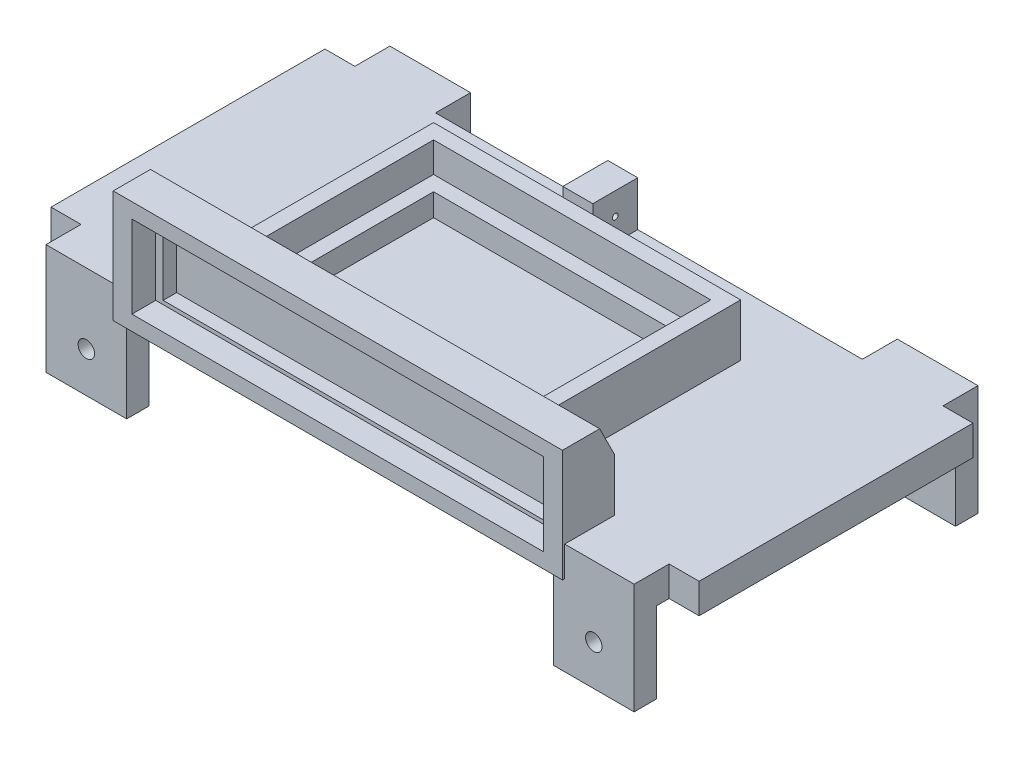
SolidWorks part; units mm, degrees
ref_plane "Front Plane" through (0, 0, 0) normal (0, 0, 1) x (1, 0, 0)
ref_plane "Top Plane" through (0, 0, 0) normal (0, 1, 0) x (1, 0, 0)
ref_plane "Right Plane" through (0, 0, 0) normal (1, 0, 0) x (0, 0, -1)
sketch "Sketch1" plane through (0, 0, 0) normal (1, 0, 0) x (0, 0, -1)
  line L0 (18.2875, 20.8275) -> (-18.2875, 20.8275)
  line L1 (14.2875, -16.8275) -> (-14.2875, -16.8275)
  line L2 (14.2875, -16.8275) -> (14.2875, 16.8275)
  line L3 (14.2875, 16.8275) -> (-14.2875, 16.8275)
  line L4 (-14.2875, -16.8275) -> (-14.2875, 16.8275)
  line L5 (14.2875, -16.8275) -> (-14.2875, 16.8275) construction
  line L6 (14.2875, 16.8275) -> (-14.2875, -16.8275) construction
  line L7 (-18.2875, -20.8275) -> (-18.2875, 20.8275)
  line L8 (18.2875, -20.8275) -> (-18.2875, -20.8275)
  line L9 (18.2875, -20.8275) -> (18.2875, 20.8275)
  point P0 (0, 0)
  dimension "D1" = 28.575
  dimension "D2" = 33.655
  dimension "D3" = 4
extrude "Boss-Extrude1" add sketch "Sketch1" along normal mid plane 82.55
sketch "Sketch2" plane through (-41.275, 0, 0) normal (-1, 0, 0) x (0, 0, 1)
  line L4 (-18.2875, 20.8275) -> (-18.2875, -20.8275)
  line L5 (-18.2875, -20.8275) -> (18.2875, -20.8275)
  line L6 (18.2875, -20.8275) -> (18.2875, 20.8275)
  line L7 (18.2875, 20.8275) -> (-18.2875, 20.8275)
  line L8 (-18.2875, 20.8275) -> (-18.2875, -20.8275)
  line L9 (-18.2875, -20.8275) -> (18.2875, -20.8275)
  line L10 (18.2875, -20.8275) -> (18.2875, 20.8275)
  line L11 (18.2875, 20.8275) -> (-18.2875, 20.8275)
  dimension "D1" = 0
extrude "Boss-Extrude2" add sketch "Sketch2" along normal blind 2
mirror "Mirror1" about plane through (0, 0, 0) normal (1, 0, 0) of "Boss-Extrude2"
sketch "Sketch4" plane through (0, -20.8275, 0) normal (0, -1, 0) x (1, 0, 0)
  line L4 (43.275, 18.2875) -> (-43.275, 18.2875)
  line L5 (-43.275, 18.2875) -> (-43.275, -18.2875)
  line L6 (-43.275, -18.2875) -> (43.275, -18.2875)
  line L7 (43.275, -18.2875) -> (43.275, 18.2875)
  line L8 (43.275, 18.2875) -> (-43.275, 18.2875)
  line L9 (-43.275, 18.2875) -> (-43.275, -18.2875)
  line L10 (-43.275, -18.2875) -> (43.275, -18.2875)
  line L11 (43.275, -18.2875) -> (43.275, 18.2875)
  dimension "D1" = 0
extrude "Cut-Extrude2" cut sketch "Sketch4" against normal blind 37.655
sketch "Sketch5" plane through (0, 0, -18.2875) normal (0, 0, -1) x (-1, 0, 0)
  line L1 (-28.4998, 6.0523) -> (-39.275, 6.0523) construction
  line L2 (-28.4998, 6.0523) -> (-28.4998, 16.8275) construction
  line L3 (-28.4998, 16.8275) -> (-39.275, 16.8275) construction
  line L4 (-39.275, 6.0523) -> (-39.275, 16.8275) construction
  line L5 (-28.4998, 6.0523) -> (-39.275, 16.8275) construction
  line L6 (-28.4998, 16.8275) -> (-39.275, 6.0523) construction
  line L7 (43.275, 16.8275) -> (-43.275, 16.8275) construction
  line L8 (-43.275, 20.8275) -> (-43.275, 16.8275) construction
  line L9 (-39.275, 16.8275) -> (-28.4998, 16.8275)
  line L10 (-31.4998, 9.0523) -> (-36.275, 9.0523) construction
  line L11 (-31.4998, 9.0523) -> (-31.4998, 13.8275) construction
  line L12 (-31.4998, 13.8275) -> (-36.275, 13.8275) construction
  line L13 (-36.275, 9.0523) -> (-36.275, 13.8275) construction
  line L14 (-31.4998, 9.0523) -> (-36.275, 13.8275) construction
  line L15 (-31.4998, 13.8275) -> (-36.275, 9.0523) construction
  line L16 (-28.4998, 16.8275) -> (-28.4998, 20.8275)
  line L17 (-43.275, 20.8275) -> (43.275, 20.8275) construction
  line L18 (-28.4998, 20.8275) -> (-39.275, 20.8275)
  line L19 (-39.275, 20.8275) -> (-39.275, 16.8275)
  point P0 (-33.8874, 11.4399)
  point P9 (-33.8874, 11.4399)
  dimension "D1" = 4
  dimension "D2" = 3
  dimension "D3" = 4.7752
extrude "Boss-Extrude3" add sketch "Sketch5" along normal blind 1.6764
sketch "Sketch6" plane through (0, 0, -19.9639) normal (0, 0, -1) x (-1, 0, 0)
  line L0 (-33.8874, 16.8275) -> (-33.8874, 6.0523) construction
  line L1 (-28.4998, 6.0523) -> (-39.275, 6.0523)
  line L2 (-28.4998, 6.0523) -> (-28.4998, 20.8275)
  line L3 (-28.4998, 20.8275) -> (-39.275, 20.8275)
  line L4 (-39.275, 6.0523) -> (-39.275, 20.8275)
  line L5 (-28.4998, 6.0523) -> (-39.275, 20.8275) construction
  line L6 (-28.4998, 20.8275) -> (-39.275, 6.0523) construction
  line L7 (-39.275, 16.8275) -> (-28.4998, 16.8275) construction
  circle A0 centre (-33.8874, 11.4399) radius 1.1
  point P0 (-33.8874, 13.4399)
  dimension "D1" = 2.2
extrude "Boss-Extrude4" add sketch "Sketch6" along normal blind 3
mirror "Mirror2" about plane through (0, 0, 0) normal (1, 0, 0) of "Boss-Extrude4", "Boss-Extrude3"
mirror "Mirror3" about plane through (0, 0, 0) normal (0, 0, 1) of "Boss-Extrude3", "Mirror2", "Boss-Extrude4"
sketch "Sketch7" plane through (0, 20.8275, 0) normal (0, 1, 0) x (1, 0, 0)
  line L0 (-5.495, 18.2875) -> (-5.495, 12.2875)
  line L1 (28.4998, 18.2875) -> (-28.4998, 18.2875) construction
  line L2 (-5.495, 12.2875) -> (-1.495, 12.2875)
  line L3 (-1.495, 12.2875) -> (-1.495, 18.2875)
  line L4 (-1.495, 18.2875) -> (-5.495, 18.2875)
  line L5 (-43.275, -18.2875) -> (-43.275, 18.2875) construction
  dimension "D1" = 37.78
  dimension "D2" = 4
  dimension "D3" = 6
extrude "Boss-Extrude5" add sketch "Sketch7" along normal blind 6
sketch "Sketch8" plane through (-1.495, 0, 0) normal (1, 0, 0) x (0, 0, -1)
  line L0 (12.2875, 23.8275) -> (18.2875, 23.8275) construction
  line L1 (12.2875, 26.8275) -> (12.2875, 20.8275) construction
  line L2 (18.2875, 26.8275) -> (18.2875, 20.8275) construction
  circle A0 centre (15.2875, 23.8275) radius 0.381
  dimension "D1" = 0.762
extrude "Cut-Extrude3" cut sketch "Sketch8" against normal through all
sketch "Sketch9" plane through (0, 20.8275, 0) normal (0, 1, 0) x (1, 0, 0)
  line L0 (28.4998, -18.2875) -> (-28.4998, -18.2875) construction
  line L1 (20.51, -18.2875) -> (-20.51, -18.2875)
  line L2 (20.51, -18.2875) -> (20.51, 10.0325)
  line L3 (20.51, 10.0325) -> (-20.51, 10.0325)
  line L4 (-20.51, -18.2875) -> (-20.51, 10.0325)
  line L5 (20.51, -18.2875) -> (-20.51, 10.0325) construction
  line L6 (20.51, 10.0325) -> (-20.51, -18.2875) construction
  line L7 (16.51, -14.2875) -> (-16.51, -14.2875)
  line L8 (16.51, -14.2875) -> (16.51, 6.0325)
  line L9 (16.51, 6.0325) -> (-16.51, 6.0325)
  line L10 (-16.51, -14.2875) -> (-16.51, 6.0325)
  line L11 (16.51, -14.2875) -> (-16.51, 6.0325) construction
  line L12 (16.51, 6.0325) -> (-16.51, -14.2875) construction
  line L13 (0, -4.1275) -> (0, -18.2875) construction
  point P0 (0, -4.1275)
  point P5 (0, -4.1275)
  dimension "D1" = 33.02
  dimension "D2" = 20.32
  dimension "D3" = 4
  dimension "D4" = 4
extrude "Boss-Extrude6" add sketch "Sketch9" along normal blind 3
sketch "Sketch10" plane through (0, 23.8275, 0) normal (0, 1, 0) x (1, 0, 0)
  line L0 (18.51, 8.0325) -> (-18.51, 8.0325)
  line L1 (-18.51, 8.0325) -> (-18.51, -16.2875)
  line L2 (-18.51, -16.2875) -> (18.51, -16.2875)
  line L3 (18.51, -16.2875) -> (18.51, 8.0325)
  line L4 (-20.51, 10.0325) -> (-20.51, -18.2875)
  line L5 (-20.51, -18.2875) -> (20.51, -18.2875)
  line L6 (20.51, -18.2875) -> (20.51, 10.0325)
  line L7 (20.51, 10.0325) -> (-20.51, 10.0325)
  line L8 (-20.51, 10.0325) -> (-20.51, -18.2875)
  line L9 (-20.51, -18.2875) -> (20.51, -18.2875)
  line L10 (20.51, -18.2875) -> (20.51, 10.0325)
  line L11 (20.51, 10.0325) -> (-20.51, 10.0325)
  dimension "D1" = 0
  dimension "D2" = 2
extrude "Boss-Extrude7" add sketch "Sketch10" along normal blind 4
sketch "Sketch11" plane through (0, 0, 0) normal (1, 0, 0) x (0, 0, -1)
  line L0 (-18.2875, 31.8275) -> (-23.2625, 31.8275)
  line L1 (-23.2625, 31.8275) -> (-23.2625, 29.8275)
  line L2 (-23.2625, 16.8275) -> (-18.2875, 16.8275)
  line L3 (-18.2875, 16.8275) -> (-18.2875, 31.8275) construction
  line L4 (-23.2625, 29.8275) -> (-20.0875, 29.8275)
  line L5 (-20.0875, 29.8275) -> (-20.0875, 18.8275) construction
  line L6 (-20.0875, 18.8275) -> (-23.2625, 18.8275)
  line L7 (-23.2625, 18.8275) -> (-23.2625, 16.8275)
  line L8 (-20.0875, 29.8275) -> (-20.0875, 29.3275)
  line L9 (-20.0875, 29.3275) -> (-18.2875, 29.3275)
  line L10 (-18.2875, 29.3275) -> (-18.2875, 19.3275)
  line L11 (-18.2875, 19.3275) -> (-20.0875, 19.3275)
  line L12 (-20.0875, 19.3275) -> (-20.0875, 18.8275)
  line L13 (-18.2875, 31.8275) -> (-16.2875, 27.8275)
  line L14 (-18.2875, 27.8275) -> (10.0325, 27.8275) construction
  line L15 (-16.2875, 27.8275) -> (-16.2875, 16.8275)
  line L16 (18.2875, 16.8275) -> (-18.2875, 16.8275) construction
  line L17 (-16.2875, 16.8275) -> (-18.2875, 16.8275)
  dimension "D1" = 0.5
  dimension "D2" = 3.175
  dimension "D3" = 10
  dimension "D4" = 2
  dimension "D5" = 1.8
extrude "Boss-Extrude8" add sketch "Sketch11" along normal mid plane 60
sketch "Sketch12" plane through (-30, 0, 0) normal (-1, 0, 0) x (0, 0, 1)
  line L0 (23.2625, 29.8275) -> (23.2625, 18.8275)
  line L1 (23.2625, 18.8275) -> (18.2875, 18.8275)
  line L2 (18.2875, 20.8275) -> (18.2875, 16.8275) construction
  line L3 (18.2875, 18.8275) -> (18.2875, 29.3275)
  line L4 (18.2875, 29.3275) -> (20.0875, 29.3275)
  line L5 (20.0875, 29.3275) -> (20.0875, 29.8275)
  line L6 (20.0875, 29.8275) -> (23.2625, 29.8275)
extrude "Boss-Extrude9" add sketch "Sketch12" against normal blind 3.5
mirror "Mirror4" about plane through (0, 0, 0) normal (1, 0, 0) of "Boss-Extrude9"
sketch "Sketch13" plane through (0, 0, 23.2625) normal (0, 0, 1) x (1, 0, 0)
  line L0 (26.5, 18.8275) -> (-26.5, 18.8275) construction
  line L1 (27.5, 18.8275) -> (-27.5, 18.8275)
  line L2 (27.5, 18.8275) -> (27.5, 29.8275)
  line L3 (27.5, 29.8275) -> (-27.5, 29.8275)
  line L4 (-27.5, 18.8275) -> (-27.5, 29.8275)
  line L5 (27.5, 18.8275) -> (-27.5, 29.8275) construction
  line L6 (27.5, 29.8275) -> (-27.5, 18.8275) construction
  line L7 (26.5, 29.8275) -> (-26.5, 29.8275) construction
  line L8 (-26.5, 18.8275) -> (-26.5, 29.8275) construction
  line L9 (26.5, 29.3275) -> (26.5, 19.3275) construction
  point P0 (0, 24.3275)
  dimension "D1" = 1
  dimension "D2" = 1
extrude "Cut-Extrude4" cut sketch "Sketch13" against normal blind 3.175
